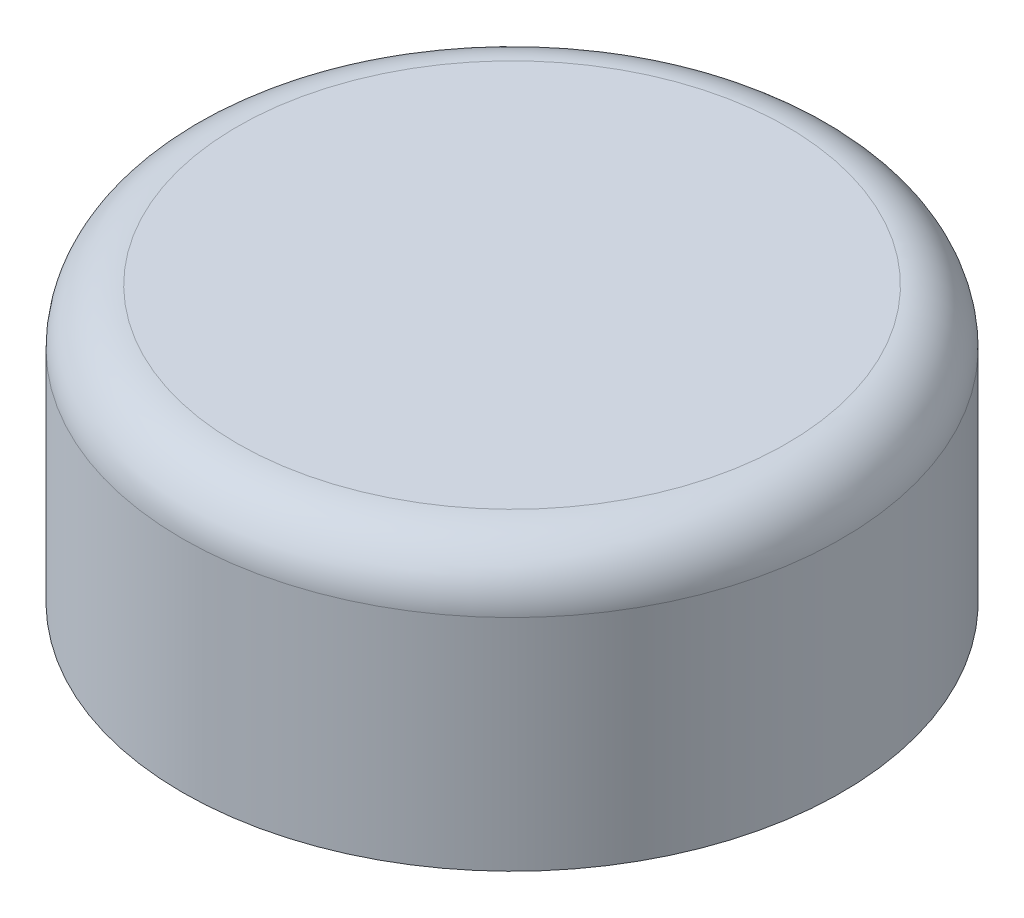
SolidWorks part; units mm, degrees
ref_plane "Front Plane" through (0, 0, 0) normal (0, 0, 1) x (1, 0, 0)
ref_plane "Top Plane" through (0, 0, 0) normal (0, 1, 0) x (1, 0, 0)
ref_plane "Right Plane" through (0, 0, 0) normal (1, 0, 0) x (0, 0, -1)
sketch "Sketch1" plane through (0, 0, 0) normal (0, 1, 0) x (1, 0, 0)
  circle A0 centre (0, 0) radius 12
  dimension "D1" = 24
extrude "Boss-Extrude1" add sketch "Sketch1" along normal blind 10
fillet "Fillet1" radius 2 1 edges at (0, 10, 12)
